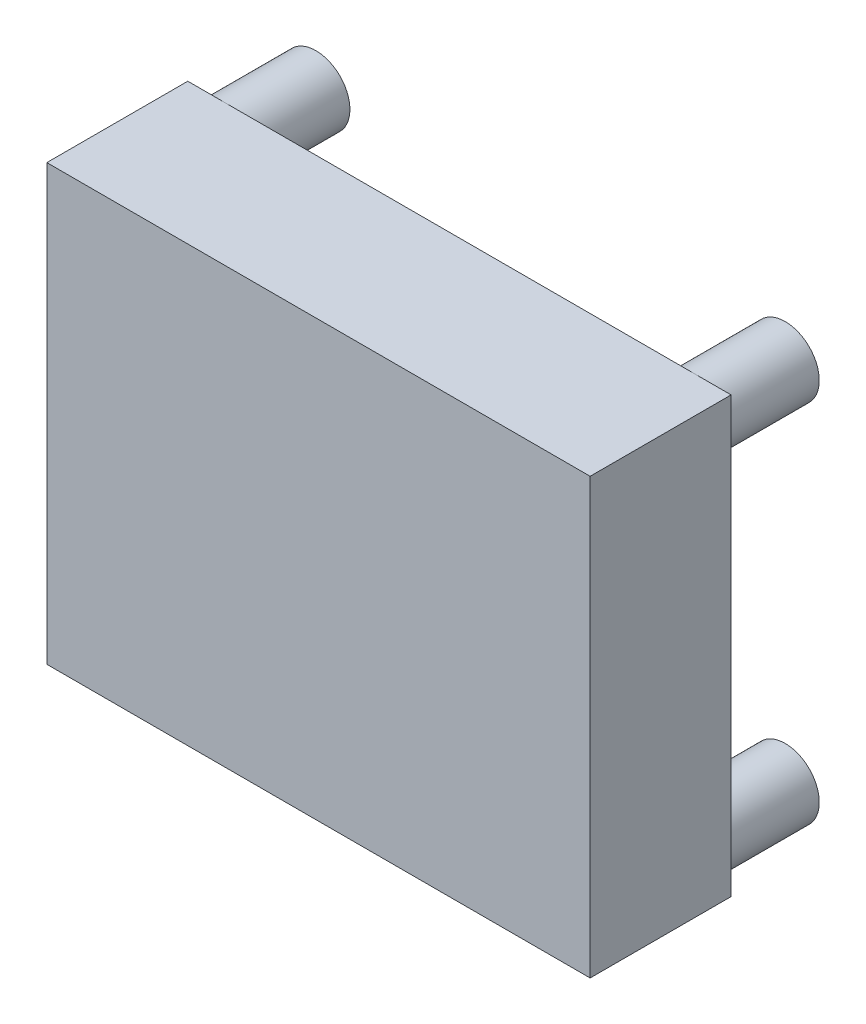
SolidWorks part; units mm, degrees
ref_plane "Front Plane" through (0, 0, 0) normal (0, 0, 1) x (1, 0, 0)
ref_plane "Top Plane" through (0, 0, 0) normal (0, 1, 0) x (1, 0, 0)
ref_plane "Right Plane" through (0, 0, 0) normal (1, 0, 0) x (0, 0, -1)
sketch "Sketch1" plane through (0, 0, 0) normal (0, 0, 1) x (1, 0, 0)
  line L1 (0, 0) -> (57.0738, 0)
  line L2 (0, 0) -> (0, 45.6438)
  line L3 (0, 45.6438) -> (57.0738, 45.6438)
  line L4 (57.0738, 0) -> (57.0738, 45.6438)
  dimension "D1" = 57.0738
  dimension "D2" = 45.6438
extrude "Boss-Extrude1" add sketch "Sketch1" along normal blind 14.8082
sketch "Sketch2" plane through (0, 0, 0) normal (0, 0, -1) x (-1, 0, 0)
  line L0 (-3.8862, 3.6322) -> (-3.8862, 0) construction
  line L1 (-53.1876, 3.6322) -> (-57.0738, 3.6322) construction
  line L2 (-57.0738, 0) -> (-57.0738, 45.6438) construction
  line L3 (0, 0) -> (-57.0738, 0) construction
  line L4 (0, 45.6438) -> (0, 0) construction
  line L5 (-53.1876, 42.0116) -> (-53.1876, 45.6438) construction
  line L6 (0, 3.6322) -> (-3.8862, 3.6322) construction
  line L7 (-53.1876, 3.6322) -> (-53.1876, 0) construction
  line L8 (-57.0738, 45.6438) -> (0, 45.6438) construction
  circle A0 centre (-3.8862, 42.0116) radius 3.5687
  circle A1 centre (-3.8862, 3.6322) radius 3.5687
  circle A2 centre (-53.1876, 3.6322) radius 3.5687
  circle A3 centre (-53.1876, 42.0116) radius 3.5687
  dimension "D5" = 7.1374
  dimension "D6" = 7.1374
  dimension "D7" = 7.1374
  dimension "D8" = 7.1374
  dimension "D1" = 3.6322
  dimension "D2" = 3.8862
  dimension "D3" = 3.8862
  dimension "D4" = 3.6322
extrude "Boss-Extrude2" add sketch "Sketch2" along normal blind 9.5758
sketch "Sketch3" plane through (0, 0, -9.5758) normal (0, 0, -1) x (-1, 0, 0)
  circle A0 centre (-3.8862, 3.6322) radius 1.3462
  circle A1 centre (-53.1876, 3.6322) radius 1.3462
  circle A2 centre (-53.1876, 42.0116) radius 1.3462
  circle A3 centre (-3.8862, 42.0116) radius 1.3462
  dimension "D1" = 2.6924
  dimension "D2" = 2.6924
  dimension "D3" = 2.6924
  dimension "D4" = 2.6924
extrude "Cut-Extrude1" cut sketch "Sketch3" against normal blind 8.89
